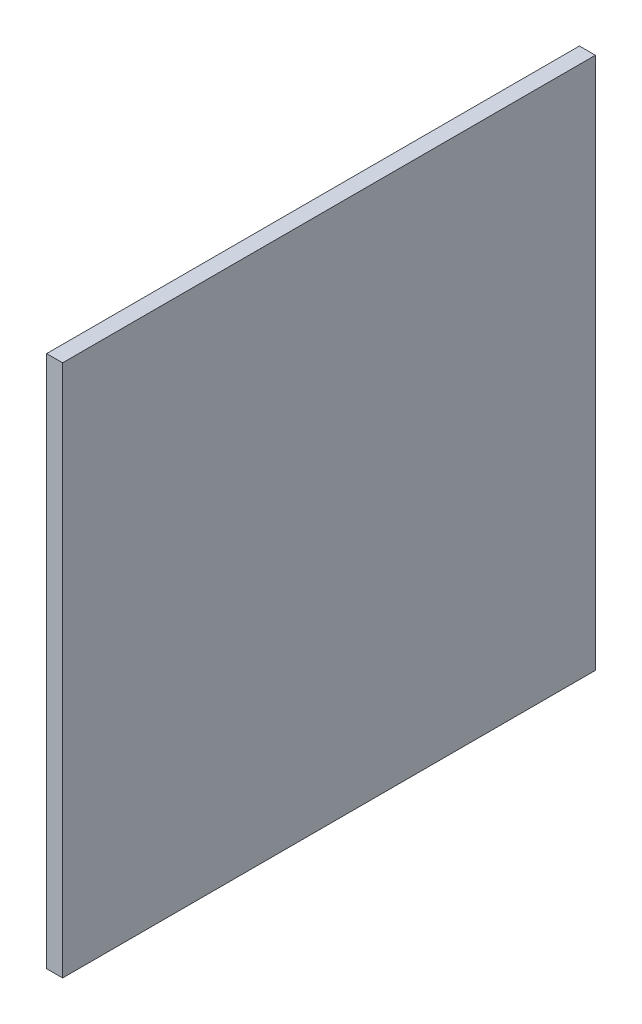
SolidWorks part; units mm, degrees
ref_plane "Front Plane" through (0, 0, 0) normal (0, 0, 1) x (1, 0, 0)
ref_plane "Top Plane" through (0, 0, 0) normal (0, 1, 0) x (1, 0, 0)
ref_plane "Right Plane" through (0, 0, 0) normal (1, 0, 0) x (0, 0, -1)
sketch "Sketch1" plane through (0, 0, 0) normal (0, 0, 1) x (1, 0, 0)
  line L1 (0, 0) -> (15, 0)
  line L2 (0, 0) -> (0, 500)
  line L3 (0, 500) -> (15, 500)
  line L4 (15, 0) -> (15, 500)
  dimension "D1" = 15
  dimension "D2" = 500
extrude "Boss-Extrude1" add sketch "Sketch1" along normal blind 500
